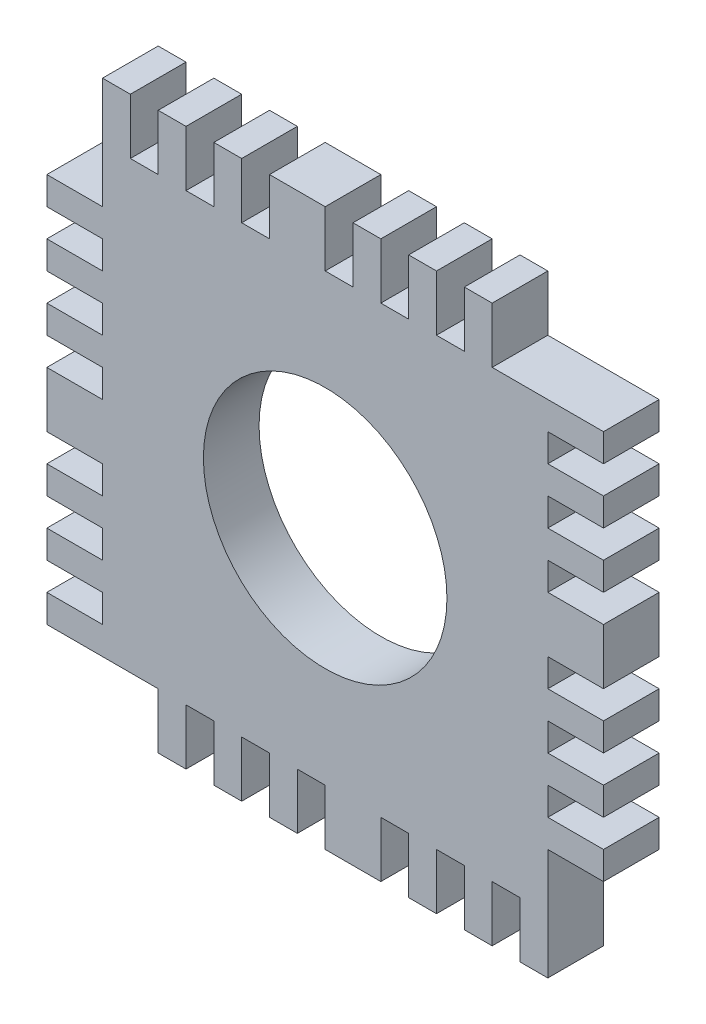
SolidWorks part; units mm, degrees
ref_plane "Plan de face" through (0, 0, 0) normal (0, 0, 1) x (1, 0, 0)
ref_plane "Plan de dessus" through (0, 0, 0) normal (0, 1, 0) x (1, 0, 0)
ref_plane "Plan de droite" through (0, 0, 0) normal (1, 0, 0) x (0, 0, -1)
sketch "Esquisse1" plane through (0, 0, 0) normal (0, 0, 1) x (1, 0, 0)
  line L0 (40, 32) -> (24, 32)
  line L1 (32, 32) -> (24, 32)
  line L2 (32, 28) -> (32, 24)
  line L3 (28, -32) -> (24, -32)
  line L4 (-32, 32) -> (-32, 24)
  line L5 (32, 32) -> (-32, -32) construction
  line L6 (0, 0) -> (-32, 32) construction
  line L8 (-32, 32) -> (-32, 40)
  line L9 (-32, 40) -> (-28, 40)
  line L10 (-28, 32) -> (-28, 40)
  line L11 (-24, 32) -> (-24, 40)
  line L13 (-20, 32) -> (-20, 40)
  line L14 (-24, 40) -> (-20, 40)
  line L15 (48, 32) -> (24, 32)
  line L16 (-16, 32) -> (-16, 40)
  line L18 (-12, 32) -> (-12, 40)
  line L19 (-16, 40) -> (-12, 40)
  line L20 (56, 32) -> (24, 32)
  line L21 (-8, 32) -> (-8, 40)
  line L24 (-8, 40) -> (-4, 40)
  line L25 (-4, 32) -> (-4, 25.7038) construction
  line L27 (4, 32) -> (4, 40)
  line L28 (8, 40) -> (4, 40)
  line L29 (8, 32) -> (8, 40)
  line L31 (12, 32) -> (12, 40)
  line L32 (16, 40) -> (12, 40)
  line L33 (16, 32) -> (16, 40)
  line L34 (24, 40) -> (20, 40)
  line L35 (20, 32) -> (20, 40)
  line L37 (24, 32) -> (24, 40)
  line L38 (32, -40) -> (32, -24)
  line L39 (-4, 32) -> (0, 32)
  line L41 (-4, 40) -> (0, 40)
  line L42 (0, 32) -> (0, 40)
  line L43 (-4, 32) -> (-4, 40) [skipped]
  line L44 (32, 32) -> (40, 32)
  line L46 (32, 28) -> (40, 28)
  line L47 (40, 32) -> (40, 28)
  line L48 (32, 24) -> (40, 24)
  line L49 (40, 24) -> (40, 20)
  line L50 (32, 20) -> (40, 20)
  line L52 (32, 16) -> (40, 16)
  line L53 (40, 16) -> (40, 12)
  line L54 (32, 12) -> (40, 12)
  line L58 (32, 0) -> (40, 0)
  line L59 (40, 4) -> (40, 0)
  line L60 (40, 8) -> (40, 4)
  line L61 (32, 8) -> (40, 8)
  line L63 (32, -4) -> (40, -4)
  line L64 (40, -8) -> (40, -4)
  line L65 (32, -8) -> (40, -8)
  line L67 (32, -12) -> (40, -12)
  line L68 (40, -16) -> (40, -12)
  line L69 (32, -16) -> (40, -16)
  line L70 (40, -24) -> (40, -20)
  line L71 (32, -20) -> (40, -20)
  line L73 (32, -24) -> (40, -24)
  line L74 (-40, -32) -> (-24, -32)
  line L75 (32, -32) -> (32, -40)
  line L77 (28, -32) -> (28, -40)
  line L78 (32, -40) -> (28, -40)
  line L79 (24, -32) -> (24, -40)
  line L80 (24, -40) -> (20, -40)
  line L81 (20, -32) -> (20, -40)
  line L83 (16, -32) -> (16, -40)
  line L84 (16, -40) -> (12, -40)
  line L85 (12, -32) -> (12, -40)
  line L89 (0, -32) -> (0, -40)
  line L90 (4, -40) -> (0, -40)
  line L91 (8, -40) -> (4, -40)
  line L92 (8, -32) -> (8, -40)
  line L94 (-4, -32) -> (-4, -40)
  line L95 (-8, -40) -> (-4, -40)
  line L96 (-8, -32) -> (-8, -40)
  line L98 (-12, -32) -> (-12, -40)
  line L99 (-16, -40) -> (-12, -40)
  line L100 (-16, -32) -> (-16, -40)
  line L101 (-24, -40) -> (-20, -40)
  line L102 (-20, -32) -> (-20, -40)
  line L104 (-24, -32) -> (-24, -40)
  line L105 (-32, 40) -> (-32, 24)
  line L106 (-32, -32) -> (-40, -32)
  line L108 (-32, -28) -> (-40, -28)
  line L109 (-40, -32) -> (-40, -28)
  line L110 (-32, -24) -> (-40, -24)
  line L111 (-40, -24) -> (-40, -20)
  line L112 (-32, -20) -> (-40, -20)
  line L114 (-32, -16) -> (-40, -16)
  line L115 (-40, -16) -> (-40, -12)
  line L116 (-32, -12) -> (-40, -12)
  line L120 (-32, 0) -> (-40, 0)
  line L121 (-40, -4) -> (-40, 0)
  line L122 (-40, -8) -> (-40, -4)
  line L123 (-32, -8) -> (-40, -8)
  line L125 (-32, 4) -> (-40, 4)
  line L126 (-40, 8) -> (-40, 4)
  line L127 (-32, 8) -> (-40, 8)
  line L129 (-32, 12) -> (-40, 12)
  line L130 (-40, 16) -> (-40, 12)
  line L131 (-32, 16) -> (-40, 16)
  line L132 (-40, 24) -> (-40, 20)
  line L133 (-32, 20) -> (-40, 20)
  line L135 (-32, 24) -> (-40, 24)
  line L136 (-24, 32) -> (-28, 32)
  line L137 (-16, 32) -> (-20, 32)
  line L138 (-16, 32) -> (-20, 32)
  line L139 (-8, 32) -> (-12, 32)
  line L140 (-8, 32) -> (-12, 32)
  line L141 (-8, 32) -> (-12, 32)
  line L142 (4, 32) -> (-4, 32)
  line L143 (4, 32) -> (-4, 32)
  line L144 (4, 32) -> (-4, 32)
  line L145 (4, 32) -> (-4, 32)
  line L146 (12, 32) -> (8, 32)
  line L147 (12, 32) -> (8, 32)
  line L148 (12, 32) -> (8, 32)
  line L149 (12, 32) -> (8, 32)
  line L150 (20, 32) -> (16, 32)
  line L151 (20, 32) -> (16, 32)
  line L152 (20, 32) -> (16, 32)
  line L153 (20, 32) -> (16, 32)
  line L154 (32, 20) -> (32, 16)
  line L155 (32, 16) -> (32, 20)
  line L156 (32, 12) -> (32, 8)
  line L157 (32, 8) -> (32, 12)
  line L158 (32, 4) -> (32, 0) [skipped]
  line L159 (32, 0) -> (32, -4)
  line L160 (32, -4) -> (32, 0)
  line L161 (32, -8) -> (32, -12)
  line L162 (-32, 20) -> (-32, 16)
  line L163 (-32, 20) -> (-32, 16)
  line L164 (-32, 12) -> (-32, 8)
  line L165 (-32, 12) -> (-32, 8)
  line L166 (-32, 4) -> (-32, 0)
  line L167 (-32, 4) -> (-32, 0)
  line L168 (-32, -8) -> (-32, -12)
  line L169 (-32, -4) -> (-32, 0) [skipped]
  line L170 (-32, -8) -> (-32, -12)
  line L171 (-32, -16) -> (-32, -20)
  line L172 (-32, -16) -> (-32, -20)
  line L173 (-32, -24) -> (-32, -28)
  line L174 (-20, -32) -> (-16, -32)
  line L175 (-24, -32) -> (-32, -32)
  line L176 (-16, -32) -> (-20, -32)
  line L177 (-12, -32) -> (-8, -32)
  line L178 (-8, -32) -> (-12, -32)
  line L179 (-4, -32) -> (0, -32)
  line L180 (0, -32) -> (-4, -32)
  line L181 (4, -32) -> (0, -32) [skipped]
  line L182 (8, -32) -> (12, -32)
  line L183 (12, -32) -> (8, -32)
  line L184 (16, -32) -> (20, -32)
  line L185 (20, -32) -> (16, -32)
  line L186 (32, -12) -> (32, -8)
  line L187 (32, -16) -> (32, -20)
  line L188 (32, -20) -> (32, -16)
  line L189 (32, -24) -> (32, -32)
  point P0 (0, 0)
  point P137 (0, 0)
  dimension "D1" = 64
  dimension "D2" = 64
  dimension "D3" = 4
  dimension "D4" = 8
  dimension "D6" = 4
  dimension "D5" = 4
  dimension "D7" = 4
extrude "Boss.-Extru.1" add sketch "Esquisse1" along normal blind 8
sketch "Esquisse2" plane through (0, 0, 0) normal (0, 0, 1) x (1, 0, 0)
  circle A0 centre (0, 0) radius 17.5
  dimension "D1" = 35
extrude "Enlèv. mat.-Extru.1" cut sketch "Esquisse2" along normal through all
